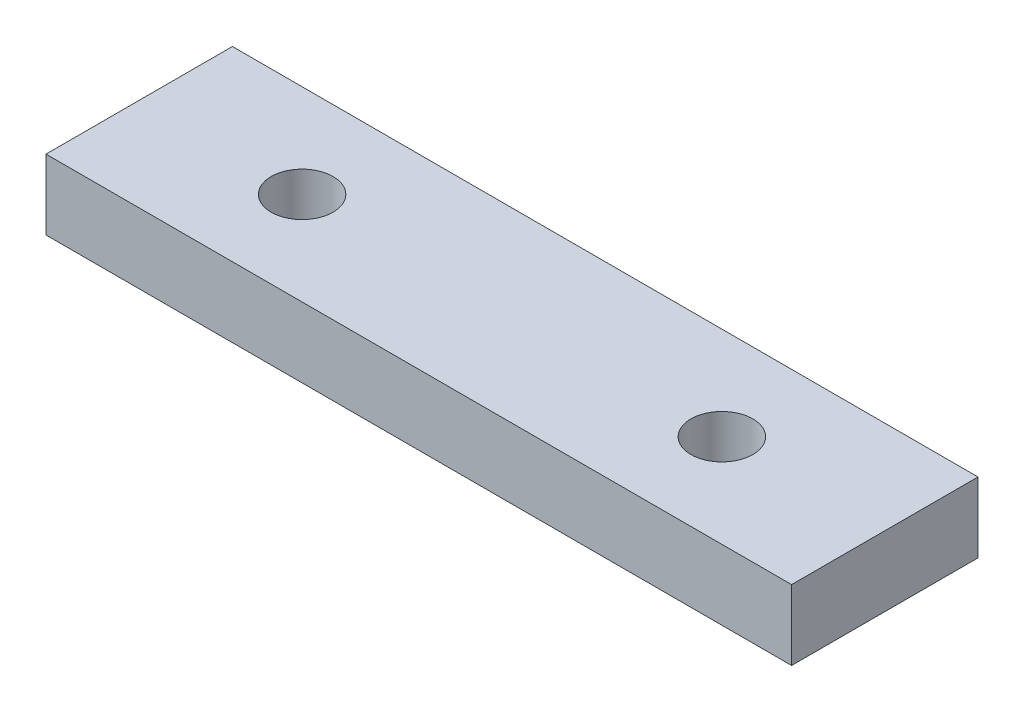
SolidWorks part; units mm, degrees
ref_plane "Front Plane" through (0, 0, 0) normal (0, 0, 1) x (1, 0, 0)
ref_plane "Top Plane" through (0, 0, 0) normal (0, 1, 0) x (1, 0, 0)
ref_plane "Right Plane" through (0, 0, 0) normal (1, 0, 0) x (0, 0, -1)
sketch "Sketch1" plane through (0, 0, 0) normal (0, 1, 0) x (1, 0, 0)
  line L1 (-25.4, 12.7) -> (25.4, 12.7)
  line L2 (-25.4, 12.7) -> (-25.4, 0)
  line L3 (-25.4, 0) -> (25.4, 0)
  line L4 (25.4, 12.7) -> (25.4, 0)
  circle A0 centre (14.3002, 6.35) radius 2.1082
  circle A1 centre (-14.3002, 6.35) radius 2.1082
  dimension "D1" = 6.35
  dimension "D2" = 4.2164
  dimension "D3" = 14.3002
  dimension "D4" = 14.3002
  dimension "D5" = 50.8
  dimension "D6" = 12.7
extrude "Boss-Extrude1" add sketch "Sketch1" along normal blind 4.7752
